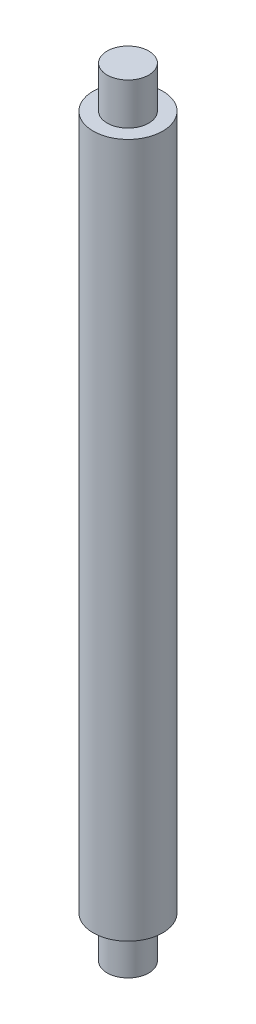
SolidWorks part; units mm, degrees
ref_plane "前视基准面" through (0, 0, 0) normal (0, 0, 1) x (1, 0, 0)
ref_plane "上视基准面" through (0, 0, 0) normal (0, 1, 0) x (1, 0, 0)
ref_plane "右视基准面" through (0, 0, 0) normal (1, 0, 0) x (0, 0, -1)
other "Configuration Table"
sketch "草图1" plane through (0, 0, 0) normal (0, 1, 0) x (1, 0, 0)
  circle A0 centre (0, 0) radius 2.5
  dimension "D1" = 5
extrude "凸台-拉伸2" add sketch "草图1" against normal mid plane 50
sketch "草图2" plane through (0, 25, 0) normal (0, 1, 0) x (1, 0, 0)
  circle A0 centre (0, 0) radius 1.5
  dimension "D1" = 3
extrude "凸台-拉伸3" add sketch "草图2" along normal blind 3
sketch "草图3" plane through (0, -25, 0) normal (0, -1, 0) x (1, 0, 0)
  circle A0 centre (0, 0) radius 1.5
  dimension "D1" = 3
extrude "凸台-拉伸4" add sketch "草图3" along normal blind 3
